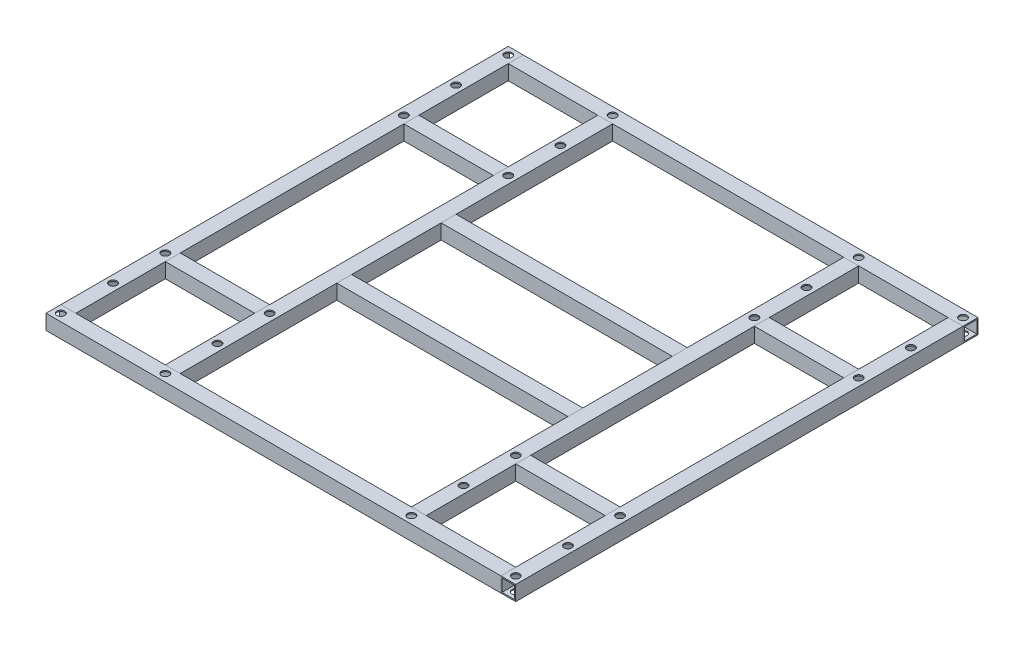
SolidWorks part; units mm, degrees
material "AISI 304"
ref_plane "Front Plane" through (0, 0, 0) normal (0, 0, 1) x (1, 0, 0)
ref_plane "Top Plane" through (0, 0, 0) normal (0, 1, 0) x (1, 0, 0)
ref_plane "Right Plane" through (0, 0, 0) normal (1, 0, 0) x (0, 0, -1)
sketch "Sketch1" plane through (0, 0, 0) normal (0, 1, 0) x (1, 0, 0)
  line L0 (0, 0) -> (0, 150) construction
  line L1 (-152.5, 150) -> (152.5, 150)
  line L2 (-152.5, 150) -> (-152.5, -150)
  line L3 (-152.5, -150) -> (152.5, -150)
  line L4 (152.5, 150) -> (152.5, -150)
  line L5 (-152.5, 150) -> (152.5, -150) construction
  line L6 (-152.5, -150) -> (152.5, 150) construction
  line L7 (82.5, 150) -> (82.5, -150)
  line L8 (152.5, -80) -> (82.5, -80)
  line L9 (82.5, 80) -> (152.5, 80)
  line L10 (-152.5, -80) -> (-82.5, -80)
  line L11 (-82.5, 80) -> (-152.5, 80)
  line L12 (-82.5, 150) -> (-82.5, -150)
  line L13 (82.5, 35) -> (-82.5, 35)
  line L14 (82.5, -35) -> (-82.5, -35)
  point P0 (0, 0)
  dimension "D1" = 300
  dimension "D2" = 305
  dimension "D3" = 70
  dimension "D4" = 70
  dimension "D5" = 70
  dimension "D6" = 70
  dimension "D7" = 35
other "Inox vuông - configured 10X0.8(1)"
ref_plane "Plane1" through (-152.5, 0, -150) normal (1, 0, 0) x (0, 0, -1)
sketch "Sketch11" plane through (-152.5, 0, -150) normal (1, 0, 0) x (0, 0, -1)
  line L0 (-4.2, 4.2) -> (4.2, 4.2)
  line L1 (-5, 5) -> (5, 5)
  line L2 (-5, 5) -> (-5, -5)
  line L3 (-5, -5) -> (5, -5)
  line L4 (5, 5) -> (5, -5)
  line L5 (-5, 5) -> (5, -5) construction
  line L6 (-5, -5) -> (5, 5) construction
  line L7 (4.2, 4.2) -> (4.2, -4.2)
  line L8 (-4.2, -4.2) -> (4.2, -4.2)
  line L9 (-4.2, 4.2) -> (-4.2, -4.2)
  point P0 (0, 0)
  point P10 (0, 5)
  point P11 (-5, 0)
  point P12 (5, 0)
  point P13 (0, -5)
  point P14 (0, 0)
  dimension "D1" = 10
  dimension "D2" = 0.8
sketch "Sketch12" plane through (0, 5, 0) normal (0, 1, 0) x (1, 0, 0)
  line L0 (-152.5, 150) -> (-152.5, -150) construction
  line L1 (-82.5, 150) -> (-82.5, -150) construction
  line L2 (0, 150) -> (0, 0) construction
  line L3 (-152.5, -150) -> (152.5, 150) construction
  line L4 (0, 0) -> (-157.5, 0) construction
  line L5 (-157.5, 155) -> (-157.5, -145) construction
  circle A0 centre (-152.5, 150) radius 2.6
  circle A1 centre (-82.5, 150) radius 2.6
  circle A2 centre (-82.5, 80) radius 2.6
  circle A3 centre (-152.5, 80) radius 2.6
  circle A4 centre (-152.5, 115) radius 2.6
  circle A5 centre (-82.5, 115) radius 2.6
  circle A6 centre (82.5, 115) radius 2.6
  circle A7 centre (152.5, 115) radius 2.6
  circle A8 centre (152.5, 80) radius 2.6
  circle A9 centre (82.5, 80) radius 2.6
  circle A10 centre (82.5, 150) radius 2.6
  circle A11 centre (152.5, 150) radius 2.6
  circle A12 centre (152.5, -150) radius 2.6
  circle A13 centre (82.5, -150) radius 2.6
  circle A14 centre (82.5, -80) radius 2.6
  circle A15 centre (152.5, -80) radius 2.6
  circle A16 centre (152.5, -115) radius 2.6
  circle A17 centre (82.5, -115) radius 2.6
  circle A18 centre (-82.5, -115) radius 2.6
  circle A19 centre (-152.5, -115) radius 2.6
  circle A20 centre (-152.5, -80) radius 2.6
  circle A21 centre (-82.5, -80) radius 2.6
  circle A22 centre (-82.5, -150) radius 2.6
  circle A23 centre (-152.5, -150) radius 2.6
  dimension "D1" = 5.2
  dimension "D2" = 35
extrude "Cut-Extrude1" cut sketch "Sketch12" against normal through all
